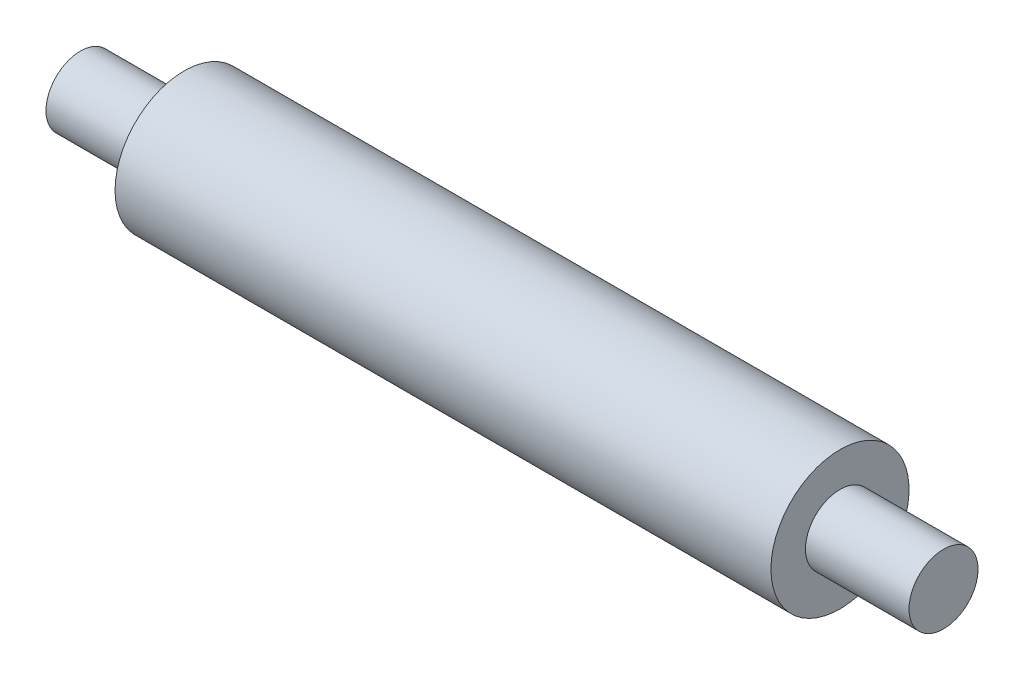
SolidWorks part; units mm, degrees
ref_plane "Front" through (0, 0, 0) normal (0, 0, 1) x (1, 0, 0)
ref_plane "Top" through (0, 0, 0) normal (0, 1, 0) x (1, 0, 0)
ref_plane "Right" through (0, 0, 0) normal (1, 0, 0) x (0, 0, -1)
sketch "草图1" plane through (0, 0, 0) normal (0, 0, 1) x (1, 0, 0)
  line L0 (-6.023, 0) -> (22.8694, 0) construction
  line L1 (-5.3563, 0) -> (-5.3563, -1)
  line L2 (-5.3563, -1) -> (-2.3563, -1)
  line L3 (-2.3563, -1) -> (-2.3563, -2)
  line L4 (-2.3563, -2) -> (16.6437, -2)
  line L5 (16.6437, -2) -> (16.6437, -1)
  line L6 (16.6437, -1) -> (19.6437, -1)
  line L7 (19.6437, -1) -> (19.6437, 0)
  line L8 (-5.3563, 0) -> (19.6437, 0)
  dimension "D1" = 1
  dimension "D2" = 2
  dimension "D3" = 19
  dimension "D4" = 3
revolve "旋转1" add sketch "草图1" angle 360 about L0
scale "缩放比例1" scale about centroid uniform scaling yes scale factor 0.683
